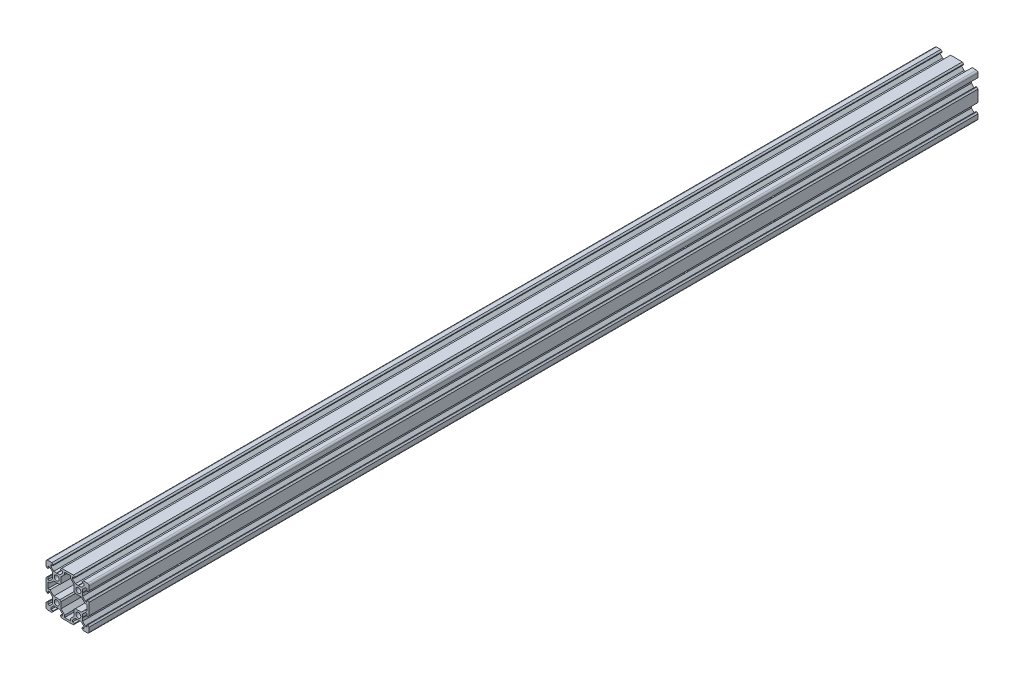
SolidWorks part; units mm, degrees
material "6063-T5"
ref_plane "Front Plane" through (0, 0, 0) normal (0, 0, 1) x (1, 0, 0)
ref_plane "Top Plane" through (0, 0, 0) normal (0, 1, 0) x (1, 0, 0)
ref_plane "Right Plane" through (0, 0, 0) normal (1, 0, 0) x (0, 0, -1)
sketch "Sketch1" plane through (0, 0, 0) normal (0, 0, 1) x (1, 0, 0)
  line L1 (18.5, -20) -> (-18.5, -20)
  line L2 (20, -18.5) -> (20, 18.5)
  line L3 (18.5, 20) -> (-18.5, 20)
  line L4 (-20, -18.5) -> (-20, 18.5)
  line L5 (20, -20) -> (-20, 20) construction
  line L6 (20, 20) -> (-20, -20) construction
  circle A0 centre (-10, 10) radius 2.3
  circle A1 centre (10, -10) radius 2.3
  circle A2 centre (10, 10) radius 2.3
  circle A3 centre (-10, -10) radius 2.3
  arc A4 (-18.5, -20) -> (-20, -18.5) centre (-18.5, -18.5) cw
  arc A5 (18.5, -20) -> (20, -18.5) centre (18.5, -18.5) ccw
  arc A6 (20, 18.5) -> (18.5, 20) centre (18.5, 18.5) ccw
  arc A7 (-18.5, 20) -> (-20, 18.5) centre (-18.5, 18.5) ccw
  point P0 (0, 0)
  line B0 (-10, 10) -> (-10, 20) construction
  line B1 (-10, 13.69) -> (-10.21, 13.9)
  line B2 (-10.21, 13.9) -> (-12.8393, 13.9)
  line B3 (-12.8393, 13.9) -> (-15.5, 16.5607)
  line B4 (-15.5, 16.5607) -> (-15.5, 18.2)
  line B5 (-15.5, 18.2) -> (-13.395, 18.2)
  line B6 (-13.395, 18.2) -> (-13.395, 18.815)
  line B7 (-13.395, 18.815) -> (-14.58, 20)
  line B8 (-14.58, 20) -> (-5.42, 20)
  line B9 (-10, 10) -> (-15.9132, 15.9132) construction
  line B10 (-6.605, 18.815) -> (-5.42, 20)
  line B11 (-6.605, 18.2) -> (-6.605, 18.815)
  line B12 (-4.5, 18.2) -> (-6.605, 18.2)
  line B13 (-4.5, 16.5607) -> (-4.5, 18.2)
  line B14 (-7.1607, 13.9) -> (-4.5, 16.5607)
  line B15 (-9.79, 13.9) -> (-7.1607, 13.9)
  line B16 (-10, 13.69) -> (-9.79, 13.9)
  line B17 (10, 10) -> (10, 20) construction
  line B18 (10, 13.69) -> (9.79, 13.9)
  line B19 (9.79, 13.9) -> (7.1607, 13.9)
  line B20 (7.1607, 13.9) -> (4.5, 16.5607)
  line B21 (4.5, 16.5607) -> (4.5, 18.2)
  line B22 (4.5, 18.2) -> (6.605, 18.2)
  line B23 (6.605, 18.2) -> (6.605, 18.815)
  line B24 (6.605, 18.815) -> (5.42, 20)
  line B25 (5.42, 20) -> (14.58, 20)
  line B26 (10, 10) -> (4.0868, 15.9132) construction
  line B27 (13.395, 18.815) -> (14.58, 20)
  line B28 (13.395, 18.2) -> (13.395, 18.815)
  line B29 (15.5, 18.2) -> (13.395, 18.2)
  line B30 (15.5, 16.5607) -> (15.5, 18.2)
  line B31 (12.8393, 13.9) -> (15.5, 16.5607)
  line B32 (10.21, 13.9) -> (12.8393, 13.9)
  line B33 (10, 13.69) -> (10.21, 13.9)
  line B34 (-10, 10) -> (-20, 10) construction
  line B35 (-13.69, 10) -> (-13.9, 9.79)
  line B36 (-13.9, 9.79) -> (-13.9, 7.1607)
  line B37 (-13.9, 7.1607) -> (-16.5607, 4.5)
  line B38 (-16.5607, 4.5) -> (-18.2, 4.5)
  line B39 (-18.2, 4.5) -> (-18.2, 6.605)
  line B40 (-18.2, 6.605) -> (-18.815, 6.605)
  line B41 (-18.815, 6.605) -> (-20, 5.42)
  line B42 (-20, 5.42) -> (-20, 14.58)
  line B43 (-10, 10) -> (-15.9132, 4.0868) construction
  line B44 (-18.815, 13.395) -> (-20, 14.58)
  line B45 (-18.2, 13.395) -> (-18.815, 13.395)
  line B46 (-18.2, 15.5) -> (-18.2, 13.395)
  line B47 (-16.5607, 15.5) -> (-18.2, 15.5)
  line B48 (-13.9, 12.8393) -> (-16.5607, 15.5)
  line B49 (-13.9, 10.21) -> (-13.9, 12.8393)
  line B50 (-13.69, 10) -> (-13.9, 10.21)
  line B51 (-10, -10) -> (-20, -10) construction
  line B52 (-13.69, -10) -> (-13.9, -10.21)
  line B53 (-13.9, -10.21) -> (-13.9, -12.8393)
  line B54 (-13.9, -12.8393) -> (-16.5607, -15.5)
  line B55 (-16.5607, -15.5) -> (-18.2, -15.5)
  line B56 (-18.2, -15.5) -> (-18.2, -13.395)
  line B57 (-18.2, -13.395) -> (-18.815, -13.395)
  line B58 (-18.815, -13.395) -> (-20, -14.58)
  line B59 (-20, -14.58) -> (-20, -5.42)
  line B60 (-10, -10) -> (-15.9132, -15.9132) construction
  line B61 (-18.815, -6.605) -> (-20, -5.42)
  line B62 (-18.2, -6.605) -> (-18.815, -6.605)
  line B63 (-18.2, -4.5) -> (-18.2, -6.605)
  line B64 (-16.5607, -4.5) -> (-18.2, -4.5)
  line B65 (-13.9, -7.1607) -> (-16.5607, -4.5)
  line B66 (-13.9, -9.79) -> (-13.9, -7.1607)
  line B67 (-13.69, -10) -> (-13.9, -9.79)
  line B68 (-10, -10) -> (-10, -20) construction
  line B69 (-10, -13.69) -> (-9.79, -13.9)
  line B70 (-9.79, -13.9) -> (-7.1607, -13.9)
  line B71 (-7.1607, -13.9) -> (-4.5, -16.5607)
  line B72 (-4.5, -16.5607) -> (-4.5, -18.2)
  line B73 (-4.5, -18.2) -> (-6.605, -18.2)
  line B74 (-6.605, -18.2) -> (-6.605, -18.815)
  line B75 (-6.605, -18.815) -> (-5.42, -20)
  line B76 (-5.42, -20) -> (-14.58, -20)
  line B77 (-10, -10) -> (-4.0868, -15.9132) construction
  line B78 (-13.395, -18.815) -> (-14.58, -20)
  line B79 (-13.395, -18.2) -> (-13.395, -18.815)
  line B80 (-15.5, -18.2) -> (-13.395, -18.2)
  line B81 (-15.5, -16.5607) -> (-15.5, -18.2)
  line B82 (-12.8393, -13.9) -> (-15.5, -16.5607)
  line B83 (-10.21, -13.9) -> (-12.8393, -13.9)
  line B84 (-10, -13.69) -> (-10.21, -13.9)
  line B85 (10, -10) -> (10, -20) construction
  line B86 (10, -13.69) -> (10.21, -13.9)
  line B87 (10.21, -13.9) -> (12.8393, -13.9)
  line B88 (12.8393, -13.9) -> (15.5, -16.5607)
  line B89 (15.5, -16.5607) -> (15.5, -18.2)
  line B90 (15.5, -18.2) -> (13.395, -18.2)
  line B91 (13.395, -18.2) -> (13.395, -18.815)
  line B92 (13.395, -18.815) -> (14.58, -20)
  line B93 (14.58, -20) -> (5.42, -20)
  line B94 (10, -10) -> (15.9132, -15.9132) construction
  line B95 (6.605, -18.815) -> (5.42, -20)
  line B96 (6.605, -18.2) -> (6.605, -18.815)
  line B97 (4.5, -18.2) -> (6.605, -18.2)
  line B98 (4.5, -16.5607) -> (4.5, -18.2)
  line B99 (7.1607, -13.9) -> (4.5, -16.5607)
  line B100 (9.79, -13.9) -> (7.1607, -13.9)
  line B101 (10, -13.69) -> (9.79, -13.9)
  line B102 (10, 10) -> (20, 10) construction
  line B103 (13.69, 10) -> (13.9, 10.21)
  line B104 (13.9, 10.21) -> (13.9, 12.8393)
  line B105 (13.9, 12.8393) -> (16.5607, 15.5)
  line B106 (16.5607, 15.5) -> (18.2, 15.5)
  line B107 (18.2, 15.5) -> (18.2, 13.395)
  line B108 (18.2, 13.395) -> (18.815, 13.395)
  line B109 (18.815, 13.395) -> (20, 14.58)
  line B110 (20, 14.58) -> (20, 5.42)
  line B111 (10, 10) -> (15.9132, 15.9132) construction
  line B112 (18.815, 6.605) -> (20, 5.42)
  line B113 (18.2, 6.605) -> (18.815, 6.605)
  line B114 (18.2, 4.5) -> (18.2, 6.605)
  line B115 (16.5607, 4.5) -> (18.2, 4.5)
  line B116 (13.9, 7.1607) -> (16.5607, 4.5)
  line B117 (13.9, 9.79) -> (13.9, 7.1607)
  line B118 (13.69, 10) -> (13.9, 9.79)
  line B119 (10, -10) -> (20, -10) construction
  line B120 (13.69, -10) -> (13.9, -9.79)
  line B121 (13.9, -9.79) -> (13.9, -7.1607)
  line B122 (13.9, -7.1607) -> (16.5607, -4.5)
  line B123 (16.5607, -4.5) -> (18.2, -4.5)
  line B124 (18.2, -4.5) -> (18.2, -6.605)
  line B125 (18.2, -6.605) -> (18.815, -6.605)
  line B126 (18.815, -6.605) -> (20, -5.42)
  line B127 (20, -5.42) -> (20, -14.58)
  line B128 (10, -10) -> (15.9132, -4.0868) construction
  line B129 (18.815, -13.395) -> (20, -14.58)
  line B130 (18.2, -13.395) -> (18.815, -13.395)
  line B131 (18.2, -15.5) -> (18.2, -13.395)
  line B132 (16.5607, -15.5) -> (18.2, -15.5)
  line B133 (13.9, -12.8393) -> (16.5607, -15.5)
  line B134 (13.9, -10.21) -> (13.9, -12.8393)
  line B135 (13.69, -10) -> (13.9, -10.21)
  line B136 (-18.2, -2.7) -> (-18.2, 2.7)
  line B137 (-18.2, 2.7) -> (-16.2393, 2.7)
  line B138 (-16.2393, 2.7) -> (-12.8393, 6.1)
  line B139 (-12.8393, 6.1) -> (-7.1607, 6.1)
  line B140 (-10, 6.1) -> (-10, 0) construction
  line B141 (-10, 0) -> (-18.2, 0) construction
  line B142 (-12.8393, -6.1) -> (-7.1607, -6.1)
  line B143 (-16.2393, -2.7) -> (-12.8393, -6.1)
  line B144 (-18.2, -2.7) -> (-16.2393, -2.7)
  line B145 (-10, 6.1) -> (-10, 10) construction
  line B146 (-10, 10) -> (-15.0927, 4.9073) construction
  line B147 (-10, 10) -> (-6.3747, 6.3747) construction
  line B148 (2.7, 18.2) -> (2.7, 16.2393)
  line B149 (2.7, 16.2393) -> (6.1, 12.8393)
  line B150 (6.1, 12.8393) -> (6.1, 7.1607)
  line B151 (-6.1, 12.8393) -> (-6.1, 7.1607)
  line B152 (-2.7, 16.2393) -> (-6.1, 12.8393)
  line B153 (-2.7, 18.2) -> (-2.7, 16.2393)
  line B154 (2.7, 18.2) -> (-2.7, 18.2)
  line B155 (2.7, -18.2) -> (-2.7, -18.2)
  line B156 (-2.7, -18.2) -> (-2.7, -16.2393)
  line B157 (-2.7, -16.2393) -> (-6.1, -12.8393)
  line B158 (-6.1, -12.8393) -> (-6.1, -7.1607)
  line B159 (6.1, -12.8393) -> (6.1, -7.1607)
  line B160 (2.7, -16.2393) -> (6.1, -12.8393)
  line B161 (2.7, -18.2) -> (2.7, -16.2393)
  line B162 (0, 18.2) -> (0, -18.2) construction
  line B163 (12.8393, -6.1) -> (7.1607, -6.1)
  line B164 (16.2393, -2.7) -> (12.8393, -6.1)
  line B165 (18.2, -2.7) -> (16.2393, -2.7)
  line B166 (18.2, -2.7) -> (18.2, 2.7)
  line B167 (18.2, 2.7) -> (16.2393, 2.7)
  line B168 (16.2393, 2.7) -> (12.8393, 6.1)
  line B169 (12.8393, 6.1) -> (7.1607, 6.1)
  line B170 (-7.1607, 6.1) -> (-6.1, 7.1607)
  line B171 (6.1, 7.1607) -> (7.1607, 6.1)
  line B172 (7.1607, -6.1) -> (6.1, -7.1607)
  line B173 (-6.1, -7.1607) -> (-7.1607, -6.1)
  dimension "D4" = 4.6
  dimension "D5" = 1.5
  dimension "D1" = 40
  dimension "D2" = 10
  dimension "D3" = 10
sketch_block_instance "V Slot 2-1"
sketch_block "V Slot 2" parameters "D1"=10, "D2"=11, "D3"=4.3, "D4"=1.8, "D5"=0.21, "D6"=45, "D7"=9.16, "D8"=1.5, "D9"=6.79
sketch_block_instance "V Slot 2-2"
sketch_block_instance "V Slot 2-3"
sketch_block_instance "V Slot 2-4"
sketch_block_instance "V Slot 2-5"
sketch_block_instance "V Slot 2-6"
sketch_block_instance "V Slot 2-7"
sketch_block_instance "V Slot 2-8"
sketch_block_instance "Center Cutout 2-1"
sketch_block "Center Cutout 2" parameters "D1"=5.4, "D2"=12.2, "D3"=8.2, "D4"=45, "D5"=10, "D6"=1.5
extrude "Boss-Extrude1" add sketch "Sketch1" along normal blind 825 contours B135 B120 B121 B122 B123 B124 B125 B126 L2 B112 B113 B114 B115 B116 B117 B118 B103 B104 B105 B106 B107 B108 B109 A6 L3 B27 B28 B29 B30 B31 B32 B33 B18 B19 B20 B21 B22 B23 B24 B10 B11 B12 B13 B14 B15 B16 B1 B2 B3
ref_plane "Plane1" through (0, 0, 412.5) normal (0, 0, 1) x (1, 0, 0)
sketch "Sketch2" plane through (20, 0, 0) normal (1, 0, 0) x (0, 0, -1)
  line L0 (-825, 0) -> (-745, 0)
  line L1 (-825, -5.42) -> (-825, 5.42) construction
  line L2 (-825, 0) -> (-255, 0) construction
  line L3 (-755, -10) -> (-735, 10) construction
  line L4 (-755, 10) -> (-735, 10) construction
  line L5 (-755, 10) -> (-755, -10) construction
  line L6 (-755, -10) -> (-735, -10) construction
  line L7 (-735, 10) -> (-735, -10) construction
  line L8 (-184.5, -10) -> (-184.5, 10) construction
  line L9 (-245, -10) -> (-265, -10) construction
  line L10 (-245, -10) -> (-245, 10) construction
  line L11 (-245, 10) -> (-265, 10) construction
  line L12 (-265, -10) -> (-265, 10) construction
  line L13 (-245, -10) -> (-265, 10) construction
  line L14 (-245, 10) -> (-265, -10) construction
  point P10 (-745, 0)
  point P18 (-184.5, 0)
  dimension "D1" = 80
  dimension "D2" = 570
  dimension "D3" = 20
  dimension "D4" = 20
  dimension "D5" = 80.5
  dimension "D6" = 20
hole_wizard "M5 Clearance Hole1" positions "3DSketch1" profile "Sketch3" hole size "M5" standard "ANSI Metric" end condition through all
sketch3d "3DSketch1"
  line L0 (20, 10, 755) -> (20, -10, 755) construction
  line L1 (20, 10, 735) -> (20, -10, 735) construction
  line L2 (20, -10, 265) -> (20, 10, 265) construction
  line L3 (20, -10, 184.5) -> (20, 10, 184.5) construction
  point P0 (20, 10, 755)
  point P4 (20, -10, 755)
  point P6 (20, -10, 735)
  point P10 (20, 10, 735)
  point P12 (20, 10, 265)
  point P16 (20, -10, 265)
  point P31 (20, 10, 184.5)
  point P35 (20, -10, 184.5)
sketch "Sketch3" plane through (20, 10, 755) normal (0, 1, 0) x (0, 0, -1)
  line L0 (0, 0) -> (0, 40)
  line L1 (0, 40) -> (2.75, 40)
  line L2 (2.75, 40) -> (2.75, 0)
  line L5 (2.75, 0) -> (0, 0)
  line L11 (0, -6.35) -> (0, 107.95) construction
  dimension "Thru Hole Dia." = 5.5
  dimension "Thru Hole Depth" = 40
